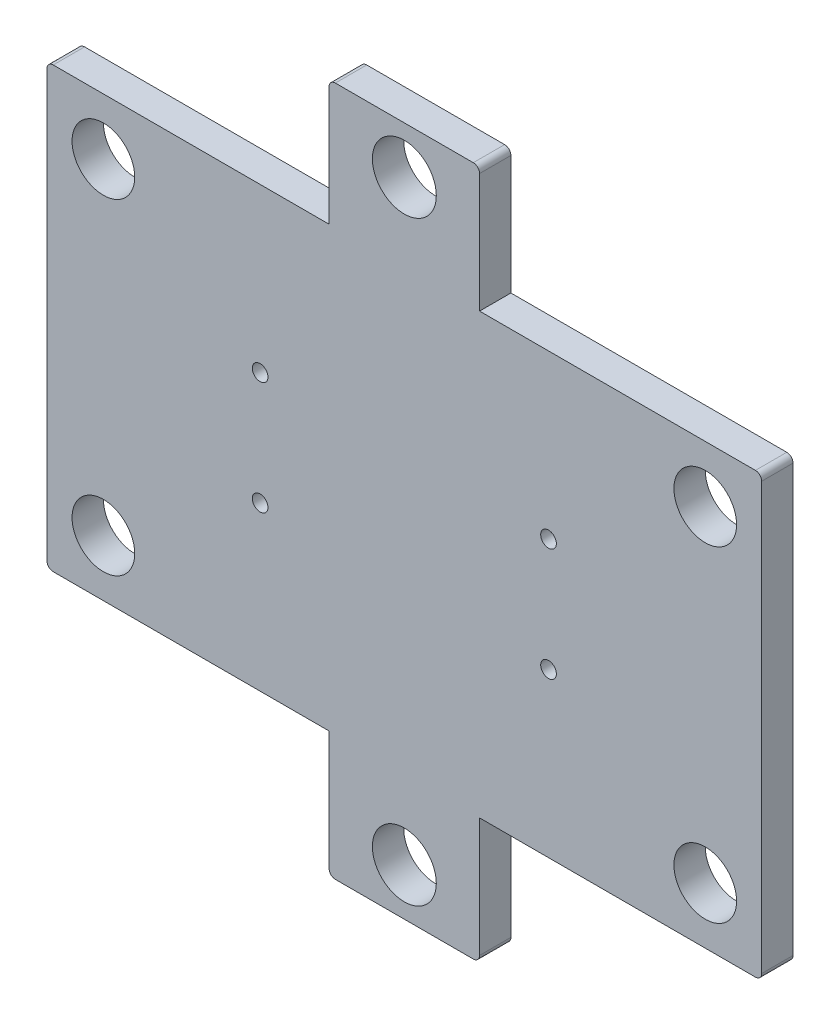
SolidWorks part; units mm, degrees
ref_plane "前视基准面" through (0, 0, 0) normal (0, 0, 1) x (1, 0, 0)
ref_plane "上视基准面" through (0, 0, 0) normal (0, 1, 0) x (1, 0, 0)
ref_plane "右视基准面" through (0, 0, 0) normal (1, 0, 0) x (0, 0, -1)
sketch "草图1" plane through (0, 0, 0) normal (0, 0, 1) x (1, 0, 0)
  line L0 (-57, 35) -> (-57, -35)
  line L1 (-57, -35) -> (-12, -35)
  line L2 (-12, -35) -> (-12, -55)
  line L3 (-12, -55) -> (12, -55)
  line L4 (12, -55) -> (12, -35)
  line L5 (12, -35) -> (57, -35)
  line L6 (57, -35) -> (57, 35)
  line L7 (57, 35) -> (12, 35)
  line L8 (12, 35) -> (12, 55)
  line L9 (12, 55) -> (-12, 55)
  line L10 (-12, 55) -> (-12, 35)
  line L11 (-12, 35) -> (-57, 35)
  line L12 (0, -1000) -> (0, 49000) construction
  line L13 (-1000, 0) -> (49000, 0) construction
  dimension "D1" = 24
  dimension "D2" = 20
  dimension "D3" = 45
  dimension "D4" = 45
  dimension "D5" = 70
  dimension "D6" = 70
  dimension "D7" = 20
  dimension "D8" = 20
  dimension "D9" = 45
  dimension "D10" = 12
  dimension "D11" = 24
  dimension "D12" = 35
extrude "凸台-拉伸1" add sketch "草图1" along normal blind 5
fillet "圆角2" radius 1 8 edges at (12, 55, 2.5) (-12, 55, 2.5) (12, -55, 2.5) (-12, -55, 2.5) (-57, 35, 2.5) (-57, -35, 2.5) (57, -35, 2.5) (57, 35, 2.5)
sketch "草图3" plane through (0, 0, 5) normal (0, 0, 1) x (1, 0, 0)
  line L0 (0, -1000) -> (0, 49000) construction
  line L1 (-12, 35) -> (-56, 35) construction
  line L2 (11, 55) -> (-11, 55) construction
  circle A0 centre (-23, 9) radius 2 construction
  circle A1 centre (-23, -9) radius 2 construction
  circle A2 centre (0, 47.5) radius 2 construction
  dimension "D1" = 23
  dimension "D2" = 18
  dimension "D4" = 7.5
  dimension "D3" = 26
hole_wizard "M3 螺纹孔的螺纹孔钻头1" positions "3D草图1" profile "草图4" hole size "M3" standard "GB" end condition through all
sketch3d "3D草图1"
  point P0 (-23, 9, 5)
  point P3 (-23, -9, 5)
sketch "草图4" plane through (-23, 9, 5) normal (1, 0, 0) x (0, -1, 0)
  line L0 (0, 0) -> (0, 5)
  line L1 (0, 5) -> (1.25, 5)
  line L2 (1.25, 5) -> (1.25, 0)
  line L5 (1.25, 0) -> (0, 0)
  line L11 (0, -6.35) -> (0, 107.95) construction
  dimension "通孔孔直径" = 2.5
  dimension "通孔孔深度" = 5
mirror "镜向1" about plane through (0, 0, 0) normal (1, 0, 0) of "M3 螺纹孔的螺纹孔钻头1"
sketch "草图5" plane through (0, 0, 5) normal (0, 0, 1) x (1, 0, 0)
  line L0 (-57, 34) -> (-57, -34) construction
  line L2 (-12, 35) -> (-56, 35) construction
  circle A0 centre (-48, 26) radius 5
  circle A1 centre (-48, -26) radius 5
  dimension "D1" = 9
  dimension "D3" = 9
  dimension "D2" = 9
  dimension "D4" = 52
extrude "切除-拉伸1" cut sketch "草图5" against normal blind 5
mirror "镜向2" about plane through (0, 0, 0) normal (1, 0, 0) of "切除-拉伸1"
hole_wizard "M12 螺纹孔的螺纹孔钻头1" positions "3D草图3" profile "草图6" hole size "M12" standard "GB" end condition through all
sketch3d "3D草图3"
  point P0 (0, 47.5, 5)
sketch "草图6" plane through (0, 47.5, 5) normal (1, 0, 0) x (0, -1, 0)
  line L0 (0, 0) -> (0, 5)
  line L1 (0, 5) -> (5.1, 5)
  line L2 (5.1, 5) -> (5.1, 0)
  line L5 (5.1, 0) -> (0, 0)
  line L11 (0, -6.35) -> (0, 107.95) construction
  dimension "通孔孔直径" = 10.2
  dimension "通孔孔深度" = 5
mirror "镜向3" about plane through (0, 0, 0) normal (0, 1, 0) of "M12 螺纹孔的螺纹孔钻头1"
